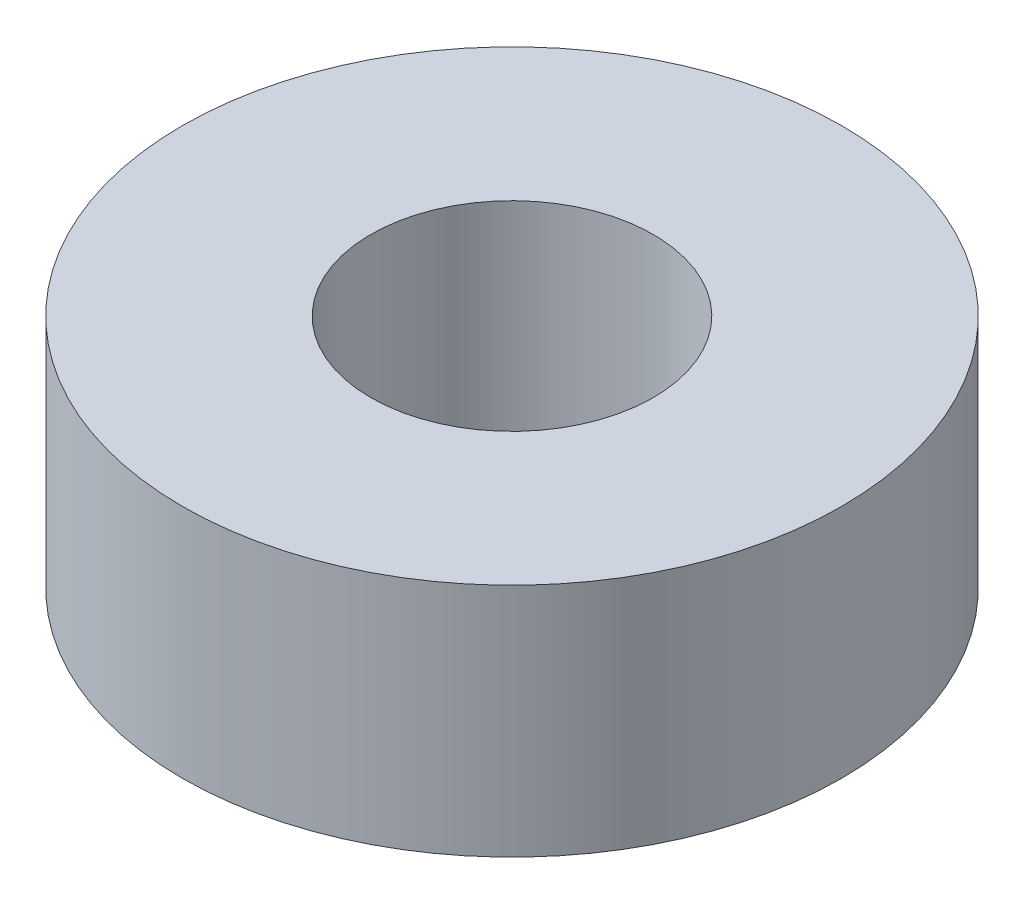
SolidWorks part; units mm, degrees
ref_plane "前视基准面" through (0, 0, 0) normal (0, 0, 1) x (1, 0, 0)
ref_plane "上视基准面" through (0, 0, 0) normal (0, 1, 0) x (1, 0, 0)
ref_plane "右视基准面" through (0, 0, 0) normal (1, 0, 0) x (0, 0, -1)
sketch "Sketch2" plane through (0, 0, 0) normal (0, 1, 0) x (1, 0, 0)
  circle A0 centre (0, 0) radius 3
  circle A1 centre (0, 0) radius 7
  dimension "D1" = 6
  dimension "D2" = 14
extrude "Boss-Extrude1" add sketch "Sketch2" along normal blind 5
